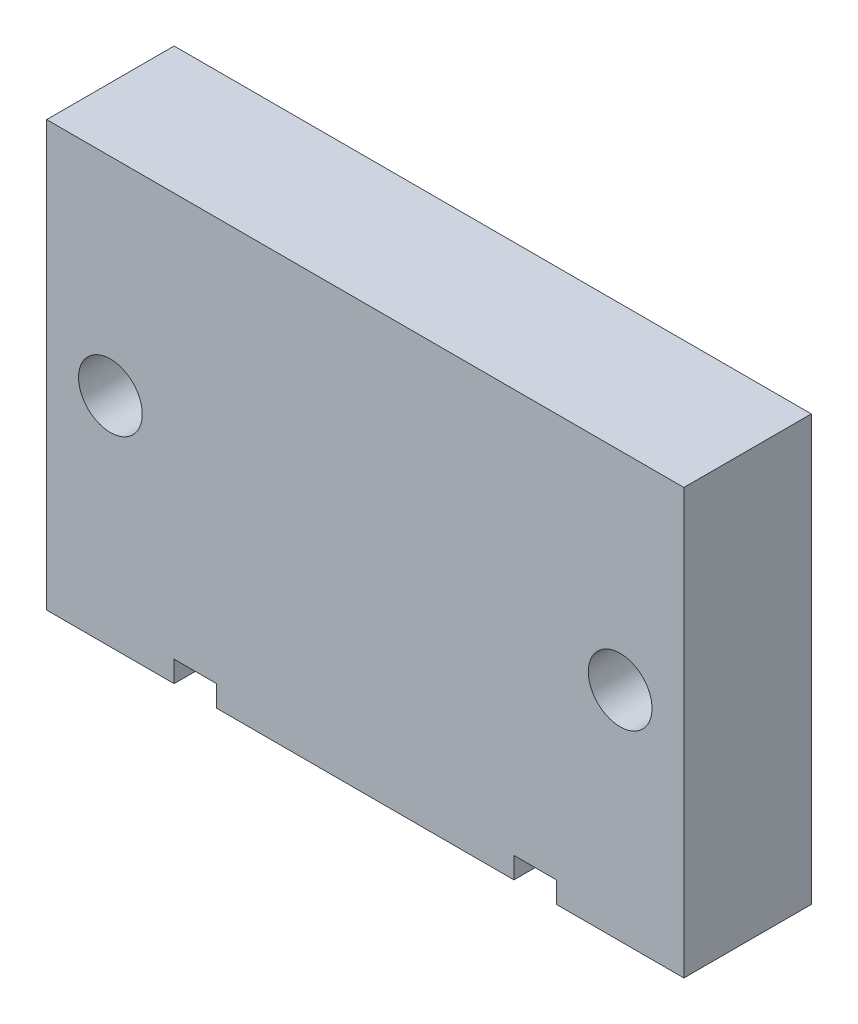
SolidWorks part; units mm, degrees
ref_plane "Alzado" through (0, 0, 0) normal (0, 0, 1) x (1, 0, 0)
ref_plane "Planta" through (0, 0, 0) normal (0, 1, 0) x (1, 0, 0)
ref_plane "Vista lateral" through (0, 0, 0) normal (1, 0, 0) x (0, 0, -1)
sketch "Croquis1" plane through (0, 0, 0) normal (0, 0, 1) x (1, 0, 0)
  line L1 (-7.5, 0) -> (7.5, 0)
  line L2 (-7.5, 0) -> (-7.5, 10)
  line L3 (-7.5, 10) -> (7.5, 10)
  line L4 (7.5, 0) -> (7.5, 10)
  point P4 (0, 0)
  dimension "D1" = 15
  dimension "D2" = 10
extrude "Saliente-Extruir1" add sketch "Croquis1" along normal mid plane 3
sketch "Croquis3" plane through (0, 0, 0) normal (0, 0, 1) x (1, 0, 0)
  line L0 (-7.5, 0) -> (7.5, 0) construction
  line L1 (3.2909, 5.12) -> (1.6454, 7.97)
  line L2 (1.6454, 7.97) -> (-1.6454, 7.97)
  line L3 (-1.6454, 7.97) -> (-3.2909, 5.12)
  line L4 (-3.2909, 5.12) -> (-1.6454, 2.27)
  line L5 (-1.6454, 2.27) -> (1.6454, 2.27)
  line L6 (1.6454, 2.27) -> (3.2909, 5.12)
  circle A0 centre (0, 5.12) radius 2.85 construction
  dimension "D1" = 5.7
  dimension "D2" = 5.12
extrude "Cortar-Extruir2" cut sketch "Croquis3" along normal blind 1 and the other way through all
sketch "Croquis4" plane through (0, 0, 0) normal (0, -1, 0) x (1, 0, 0)
  line L0 (-7.5, 1.5) -> (7.5, 1.5) construction
  line L1 (-3.5, 1.5) -> (-4.5, 1.5)
  line L2 (-3.5, 1.5) -> (-3.5, -1.5)
  line L3 (-3.5, -1.5) -> (-4.5, -1.5)
  line L4 (-4.5, 1.5) -> (-4.5, -1.5)
  line L5 (-7.5, -1.5) -> (7.5, -1.5) construction
  line L7 (4.5, 1.5) -> (3.5, 1.5)
  line L8 (4.5, 1.5) -> (4.5, -1.5)
  line L9 (4.5, -1.5) -> (3.5, -1.5)
  line L10 (3.5, 1.5) -> (3.5, -1.5)
  line L12 (-7.5, 1.5) -> (-7.5, -1.5) construction
  line L13 (7.5, 1.5) -> (7.5, -1.5) construction
  dimension "D1" = 3
  dimension "D2" = 3
  dimension "D3" = 1
  dimension "D4" = 1
extrude "Cortar-Extruir3" cut sketch "Croquis4" against normal blind 0.5
sketch "Croquis6" plane through (0, 0, -1.5) normal (0, 0, -1) x (-1, 0, 0)
  line L0 (-4.5, 0) -> (-7.5, 0) construction
  circle A0 centre (-6, 5.12) radius 0.75
  circle A1 centre (6, 5.12) radius 0.75
  point P4 (0, 0)
  dimension "D3" = 1.5
  dimension "D4" = 1.5
  dimension "D5" = 5.12
  dimension "D1" = 6
  dimension "D2" = 6
extrude "Cortar-Extruir6" cut sketch "Croquis6" against normal through all
